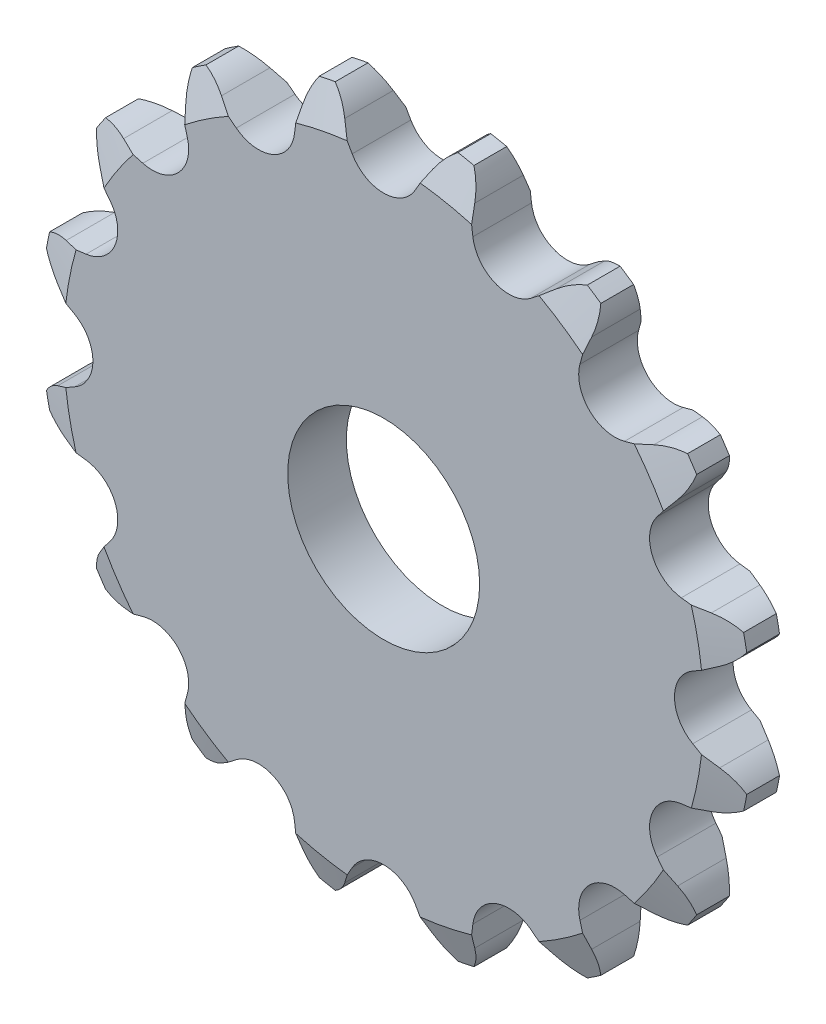
SolidWorks part; units mm, degrees
material "Plain Carbon Steel"
ref_plane "Front Plane" through (0, 0, 0) normal (0, 0, 1) x (1, 0, 0)
ref_plane "Top Plane" through (0, 0, 0) normal (0, 1, 0) x (1, 0, 0)
ref_plane "Right Plane" through (0, 0, 0) normal (1, 0, 0) x (0, 0, -1)
sketch "Sketch1" plane through (0, 0, 0) normal (0, 0, 1) x (1, 0, 0)
  circle A0 centre (0, 0) radius 25.4
  dimension "D1" = 50.8
extrude "Extrude1" add sketch "Sketch1" along normal mid plane 4.191
chamfer "Chamfer1" distance 2.54 angle 20 1 edges at (25.4, 0, 2.0955)
chamfer "Chamfer2" distance 2.54 angle 20 1 edges at (25.4, 0, -2.0955)
sketch "Sketch2" plane through (0, 0, 0) normal (0, 0, 1) x (1, 0, 0)
  line L1 (-2.2499, 22.0834) -> (-3.142, 23.6459)
  line L2 (0, 0) -> (0, 23.368) construction
  line L3 (2.2499, 22.0834) -> (3.142, 23.6459)
  arc A0 (3.142, 23.6459) -> (4.3826, 25.0191) centre (6.8919, 21.505) cw
  arc A1 (-3.142, 23.6459) -> (-4.3826, 25.0191) centre (-6.8919, 21.505) ccw
  arc A2 (-2.2499, 22.0834) -> (2.2499, 22.0834) centre (0, 23.368) ccw
  arc A3 (4.3826, 25.0191) -> (-4.3826, 25.0191) centre (0, 0) ccw
  circle A4 centre (0, 0) radius 25.4 construction
  dimension "D1" = 2.5908
  dimension "D4" = 4.318
  dimension "D9" = 8.7652
  dimension "D2" = 13.7837
  dimension "D3" = 2.032
extrude "Extrude2" cut sketch "Sketch2" against normal through all and the other way through all
pattern_circular "CirPattern1" count 16 over 360 about axis through (0, 0, 0) along (0, 0, 1) of "Extrude2"
sketch "Sketch3" plane through (0, 0, 2.0955) normal (0, 0, 1) x (1, 0, 0)
  circle A0 centre (0, 0) radius 6.858
  dimension "D1" = 13.716
extrude "Extrude3" cut sketch "Sketch3" against normal through all
cosmetic thread "Cosmetic Thread1" parameters "D2"=13.716
sketch "Sketch6" plane through (0, 0, 0) normal (0, 0, 1) x (1, 0, 0)
  circle A0 centre (0, 0) radius 23.368
